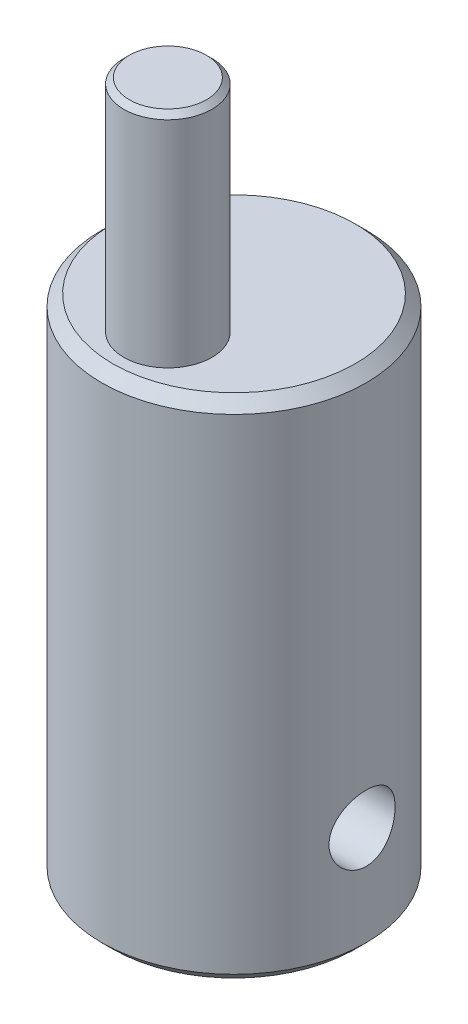
SolidWorks part; units mm, degrees
ref_plane "Front Plane" through (0, 0, 0) normal (0, 0, 1) x (1, 0, 0)
ref_plane "Top Plane" through (0, 0, 0) normal (0, 1, 0) x (1, 0, 0)
ref_plane "Right Plane" through (0, 0, 0) normal (1, 0, 0) x (0, 0, -1)
sketch "Sketch1" plane through (0, 0, 0) normal (0, 1, 0) x (1, 0, 0)
  circle A0 centre (0, 0) radius 6
  dimension "D1" = 12
extrude "Boss-Extrude1" add sketch "Sketch1" along normal blind 23
sketch "Sketch2" plane through (0, 23, 0) normal (0, 1, 0) x (1, 0, 0)
  circle A0 centre (0, -3) radius 2
  dimension "D2" = 4
  dimension "D1" = 3
extrude "Boss-Extrude2" add sketch "Sketch2" along normal blind 10
sketch "Sketch3" plane through (0, 0, 0) normal (1, 0, 0) x (0, 0, -1)
  circle A0 centre (0, 5) radius 1.5
  point P2 (0, 0)
  dimension "D1" = 3
  dimension "D2" = 5
extrude "Cut-Extrude1" cut sketch "Sketch3" against normal mid plane 29
chamfer "Chamfer1" distance 0.25 angle 45 1 edges at (0, 33, 5)
chamfer "Chamfer2" distance 0.5 angle 45 1 edges at (0, 23, 6)
chamfer "Chamfer3" distance 0.5 angle 45 1 edges at (0, 0, 6)
